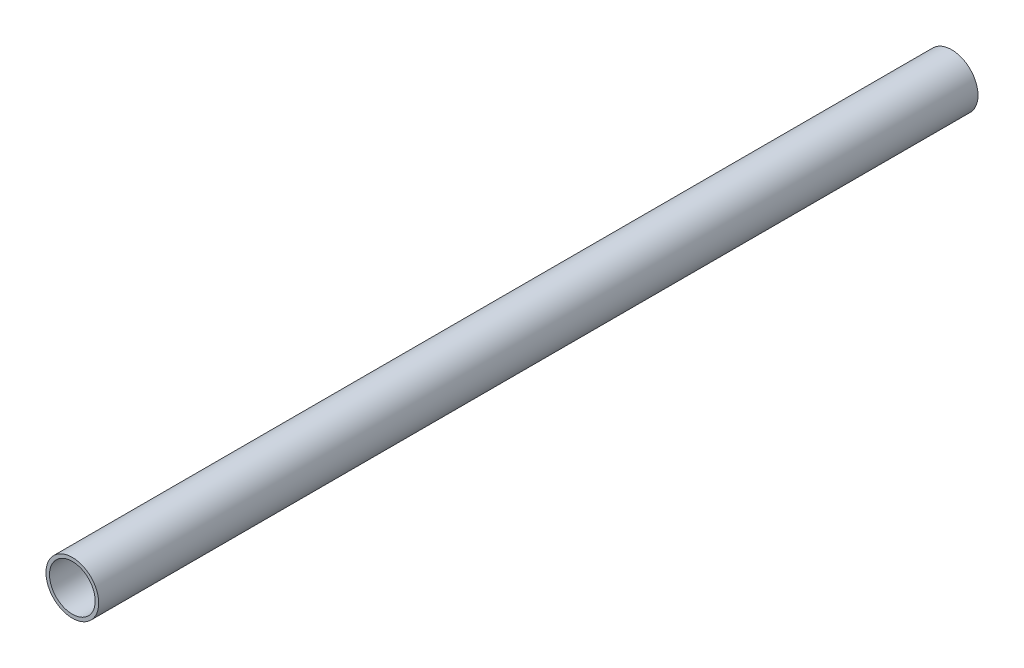
SolidWorks part; units mm, degrees
ref_plane "Front Plane" through (0, 0, 0) normal (0, 0, 1) x (1, 0, 0)
ref_plane "Top Plane" through (0, 0, 0) normal (0, 1, 0) x (1, 0, 0)
ref_plane "Right Plane" through (0, 0, 0) normal (1, 0, 0) x (0, 0, -1)
sketch "Sketch1" plane through (0, 0, 0) normal (0, 0, 1) x (1, 0, 0)
  circle A0 centre (0, 0) radius 1.5
  circle A1 centre (0, 0) radius 1.3
  dimension "D1" = 3
  dimension "D2" = 2.6
extrude "Boss-Extrude1" add sketch "Sketch1" along normal blind 50
